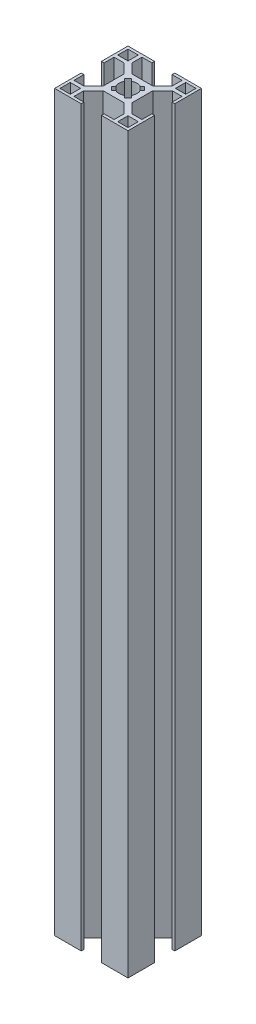
SolidWorks part; units mm, degrees
material "3.0255 (EN-AW 1350A)"
ref_plane "Alzado" through (0, 0, 0) normal (0, 0, 1) x (1, 0, 0)
ref_plane "Planta" through (0, 0, 0) normal (0, 1, 0) x (1, 0, 0)
ref_plane "Vista lateral" through (0, 0, 0) normal (1, 0, 0) x (0, 0, -1)
sketch "Croquis2" plane through (0, 0, 0) normal (0, 1, 0) x (1, 0, 0)
  line L0 (-12.6732, 23.1711) -> (-8.4732, 23.1711)
  line L1 (-37.3732, 24.2711) -> (-26.4982, 24.2711)
  line L2 (-37.3732, 24.2711) -> (-37.3732, 13.3961)
  line L3 (-37.3732, -5.7289) -> (-26.4982, -5.7289)
  line L4 (-7.3732, 24.2711) -> (-7.3732, 13.3961)
  line L5 (-30.5732, -4.6289) -> (-26.4982, -4.6289)
  line L6 (-30.5732, 23.1711) -> (-26.4982, 23.1711)
  line L7 (-36.2732, 5.1461) -> (-37.3732, 5.1461)
  line L8 (-8.4732, 23.1711) -> (-8.4732, 18.9711)
  line L9 (-36.2732, -4.6289) -> (-32.0732, -4.6289)
  line L10 (-36.2732, 23.1711) -> (-36.2732, 18.9711)
  line L11 (-36.2732, 23.1711) -> (-32.0732, 23.1711)
  line L12 (-32.0732, -0.4289) -> (-36.2732, -0.4289)
  line L15 (-8.4732, 18.9711) -> (-12.6732, 18.9711)
  line L16 (-12.6732, 23.1711) -> (-12.6732, 18.9711)
  line L17 (-32.0732, -0.4289) -> (-32.0732, -4.6289)
  line L19 (-36.2732, -0.4289) -> (-36.2732, -4.6289)
  line L21 (-32.0732, 23.1711) -> (-32.0732, 18.9711)
  line L22 (-32.0732, 18.9711) -> (-36.2732, 18.9711)
  line L24 (-8.4732, -0.4289) -> (-12.6732, -0.4289)
  line L25 (-8.4732, -0.4289) -> (-8.4732, -4.6289)
  line L26 (-8.4732, -4.6289) -> (-12.6732, -4.6289)
  line L27 (-12.6732, -0.4289) -> (-12.6732, -4.6289)
  line L28 (-26.5862, 3.3611) -> (-18.1603, 3.3611)
  line L29 (-16.4632, 13.4841) -> (-16.4632, 5.0582)
  line L30 (-26.5862, 15.1811) -> (-18.1603, 15.1811)
  line L31 (-28.2832, 13.4841) -> (-28.2832, 5.0582)
  line L32 (-28.2832, 15.1811) -> (-16.4632, 15.1811) construction
  line L33 (-28.2832, 3.3611) -> (-16.4632, 3.3611) construction
  line L34 (-7.3732, 5.1461) -> (-8.4732, 5.1461)
  line L35 (-7.3732, 13.3961) -> (-8.4732, 13.3961)
  line L36 (-26.4982, 24.2711) -> (-26.4982, 23.1711)
  line L37 (-18.2482, 24.2711) -> (-18.2482, 23.1711)
  line L38 (-36.2732, 13.3961) -> (-37.3732, 13.3961)
  line L39 (-19.1655, 11.0646) -> (-18.2482, 11.9819)
  line L40 (-36.2732, 5.1461) -> (-36.2732, 1.0711)
  line L41 (-36.2732, 23.1711) -> (-36.2732, -4.6289) construction
  line L42 (-37.3732, 5.1461) -> (-37.3732, -5.7289)
  line L43 (-37.3732, 24.2711) -> (-37.3732, -5.7289) construction
  line L44 (-18.2482, -4.6289) -> (-18.2482, -5.7289)
  line L46 (-8.4732, 5.1461) -> (-8.4732, 1.0711)
  line L47 (-8.4732, 23.1711) -> (-8.4732, -4.6289) construction
  line L48 (-7.3732, 5.1461) -> (-7.3732, -5.7289)
  line L49 (-7.3732, 24.2711) -> (-7.3732, -5.7289) construction
  line L51 (-25.084, 5.1461) -> (-24.1667, 6.0634)
  line L52 (-18.2482, -4.6289) -> (-14.1732, -4.6289)
  line L53 (-36.2732, -4.6289) -> (-8.4732, -4.6289) construction
  line L54 (-18.2482, -5.7289) -> (-7.3732, -5.7289)
  line L55 (-37.3732, -5.7289) -> (-7.3732, -5.7289) construction
  line L56 (-16.4632, 15.1811) -> (-16.4632, 3.3611) construction
  line L57 (-26.4982, 11.9819) -> (-25.5809, 11.0646)
  line L58 (-18.2482, 23.1711) -> (-14.1732, 23.1711)
  line L59 (-36.2732, 23.1711) -> (-8.4732, 23.1711) construction
  line L60 (-18.2482, 24.2711) -> (-7.3732, 24.2711)
  line L61 (-37.3732, 24.2711) -> (-7.3732, 24.2711) construction
  line L62 (-32.2703, 1.0711) -> (-36.2732, 1.0711)
  line L63 (-30.5732, 1.0711) -> (-37.7732, 1.0711) construction
  line L64 (-30.5732, 1.0711) -> (-30.5732, -6.1289) construction
  line L65 (-30.5732, -0.6259) -> (-30.5732, -4.6289)
  line L66 (-8.4732, 1.0711) -> (-12.4762, 1.0711)
  line L67 (-14.1732, -0.6259) -> (-14.1732, -4.6289)
  line L68 (-6.9732, 1.0711) -> (-6.9732, -6.1289) construction
  line L69 (-30.5732, -0.6259) -> (-26.5862, 3.3611)
  line L70 (-6.9732, 17.4711) -> (-14.1732, 17.4711) construction
  line L71 (-8.4732, 17.4711) -> (-12.4762, 17.4711)
  line L72 (-14.1732, 23.1711) -> (-14.1732, 19.1682)
  line L73 (-8.4732, 17.4711) -> (-8.4732, 13.3961)
  line L74 (-32.2703, 17.4711) -> (-36.2732, 17.4711)
  line L75 (-30.5732, 24.6711) -> (-30.5732, 17.4711) construction
  line L76 (-16.4632, 13.4841) -> (-12.4762, 17.4711)
  line L77 (-30.5732, 23.1711) -> (-30.5732, 19.1682)
  line L78 (-30.5732, -6.1289) -> (-37.7732, -6.1289) construction
  line L79 (-37.7732, 1.0711) -> (-37.7732, -6.1289) construction
  line L80 (-26.4982, -4.6289) -> (-26.4982, -5.7289)
  line L81 (-30.5732, 19.1682) -> (-26.5862, 15.1811)
  line L83 (-18.1603, 3.3611) -> (-14.1732, -0.6259)
  line L84 (-30.5732, 17.4711) -> (-37.7732, 17.4711) construction
  line L85 (-37.7732, 24.6711) -> (-37.7732, 17.4711) construction
  line L86 (-30.5732, 24.6711) -> (-37.7732, 24.6711) construction
  line L87 (-36.2732, 17.4711) -> (-36.2732, 13.3961)
  line L88 (-32.2703, 1.0711) -> (-28.2832, 5.0582)
  line L90 (-6.9732, -6.1289) -> (-14.1732, -6.1289) construction
  line L91 (-14.1732, 1.0711) -> (-14.1732, -6.1289) construction
  line L92 (-6.9732, 1.0711) -> (-14.1732, 1.0711) construction
  line L94 (-25.084, 13.3961) -> (-24.1667, 12.4788)
  line L95 (-19.1655, 7.4777) -> (-18.2482, 6.5603)
  line L96 (-20.5798, 6.0634) -> (-19.6624, 5.1461)
  line L97 (-14.1732, 24.6711) -> (-14.1732, 17.4711) construction
  line L98 (-6.9732, 24.6711) -> (-14.1732, 24.6711) construction
  line L99 (-6.9732, 24.6711) -> (-6.9732, 17.4711) construction
  line L100 (-16.4632, 5.0582) -> (-12.4762, 1.0711)
  line L101 (-26.4982, 6.5603) -> (-25.5809, 7.4777)
  line L104 (-28.2832, 15.1811) -> (-28.2832, 3.3611) construction
  line L105 (-18.1603, 15.1811) -> (-14.1732, 19.1682)
  line L106 (-32.2703, 17.4711) -> (-28.2832, 13.4841)
  line L111 (-20.5798, 12.4788) -> (-19.6624, 13.3961)
  line L114 (-26.4982, 6.5603) -> (-25.084, 5.1461)
  line L115 (-19.6624, 5.1461) -> (-18.2482, 6.5603)
  line L116 (-19.6624, 13.3961) -> (-18.2482, 11.9819)
  line L117 (-25.084, 13.3961) -> (-26.4982, 11.9819)
  line L119 (-32.0732, 23.1711) -> (-36.2732, 23.1711) construction
  line L120 (-8.4732, 23.1711) -> (-12.6732, 23.1711) construction
  line L121 (-32.0732, -4.6289) -> (-36.2732, -4.6289) construction
  line L122 (-8.4732, 23.1711) -> (-8.4732, 18.9711) construction
  line L123 (-36.2732, 23.1711) -> (-36.2732, 18.9711) construction
  arc A0 (-25.5809, 11.0646) -> (-25.5809, 7.4777) centre (-22.3732, 9.2711) ccw
  arc A1 (-20.5798, 12.4788) -> (-24.1667, 12.4788) centre (-22.3732, 9.2711) ccw
  arc A2 (-19.1655, 7.4777) -> (-19.1655, 11.0646) centre (-22.3732, 9.2711) ccw
  arc A3 (-24.1667, 6.0634) -> (-20.5798, 6.0634) centre (-22.3732, 9.2711) ccw
  dimension "D1" = 30
  dimension "D2" = 30
  dimension "D5" = 1.5
extrude "Saliente-Extruir1" add sketch "Croquis2" along normal blind 300
